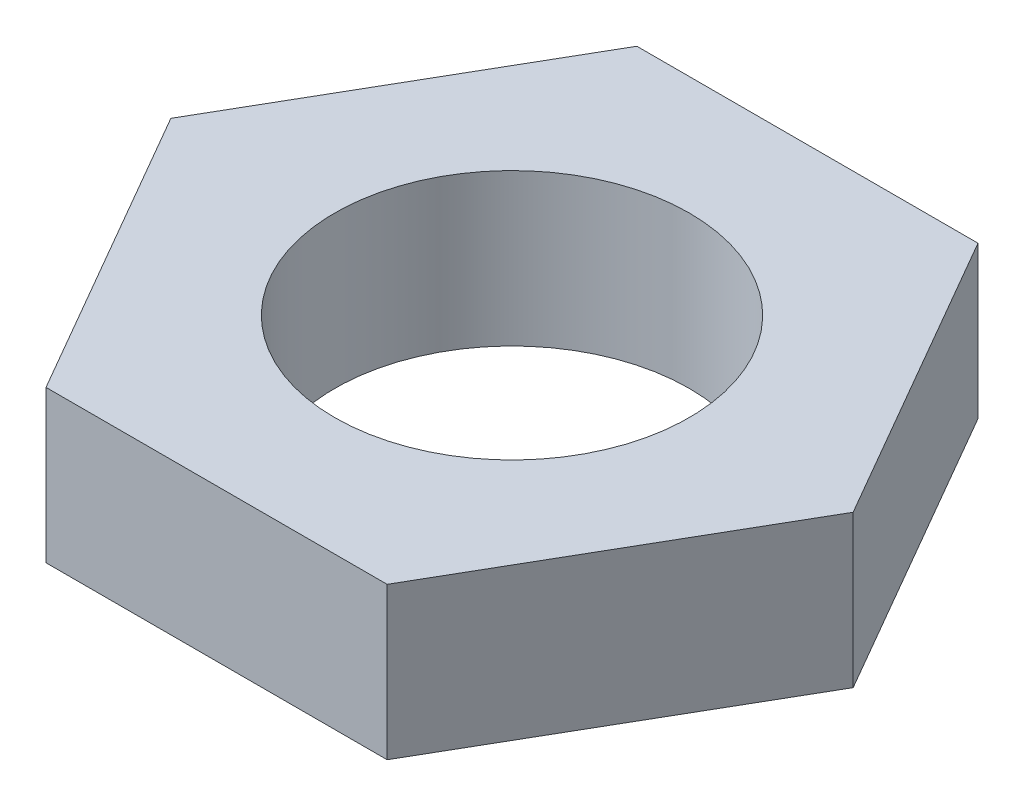
SolidWorks part; units mm, degrees
ref_plane "Front Plane" through (0, 0, 0) normal (0, 0, 1) x (1, 0, 0)
ref_plane "Top Plane" through (0, 0, 0) normal (0, 1, 0) x (1, 0, 0)
ref_plane "Right Plane" through (0, 0, 0) normal (1, 0, 0) x (0, 0, -1)
sketch "Sketch1" plane through (0, 0, 0) normal (0, 1, 0) x (1, 0, 0)
  line L1 (4.0415, 0) -> (2.0207, 3.5)
  line L2 (2.0207, 3.5) -> (-2.0207, 3.5)
  line L3 (-2.0207, 3.5) -> (-4.0415, 0)
  line L4 (-4.0415, 0) -> (-2.0207, -3.5)
  line L5 (-2.0207, -3.5) -> (2.0207, -3.5)
  line L6 (2.0207, -3.5) -> (4.0415, 0)
  circle A0 centre (0, 0) radius 3.5 construction
  circle A1 centre (0, 0) radius 2.1
  dimension "D2" = 4.2
  dimension "D1" = 7
extrude "Boss-Extrude1" add sketch "Sketch1" along normal blind 1.8
